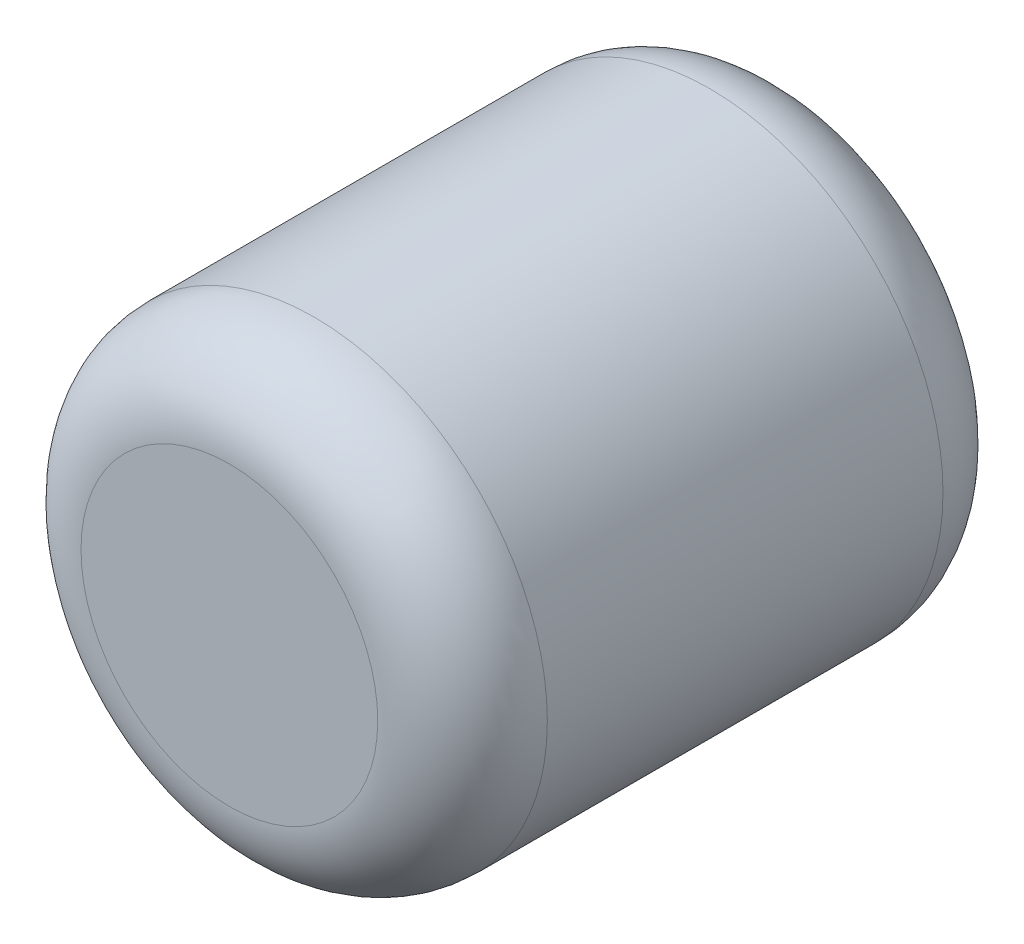
SolidWorks part; units mm, degrees
ref_plane "Front Plane" through (0, 0, 0) normal (0, 0, 1) x (1, 0, 0)
ref_plane "Top Plane" through (0, 0, 0) normal (0, 1, 0) x (1, 0, 0)
ref_plane "Right Plane" through (0, 0, 0) normal (1, 0, 0) x (0, 0, -1)
sketch "Sketch2" plane through (0, 0, 0) normal (0, 0, 1) x (1, 0, 0)
  circle A0 centre (0, 0) radius 8.25
  dimension "D1" = 16.5
extrude "Boss-Extrude1" add sketch "Sketch2" along normal blind 20
ref_point "Point1"
ref_point "Point2"
fillet "Fillet1" radius 3 2 edges at (8.25, 0, 20) (8.25, 0, 0)
